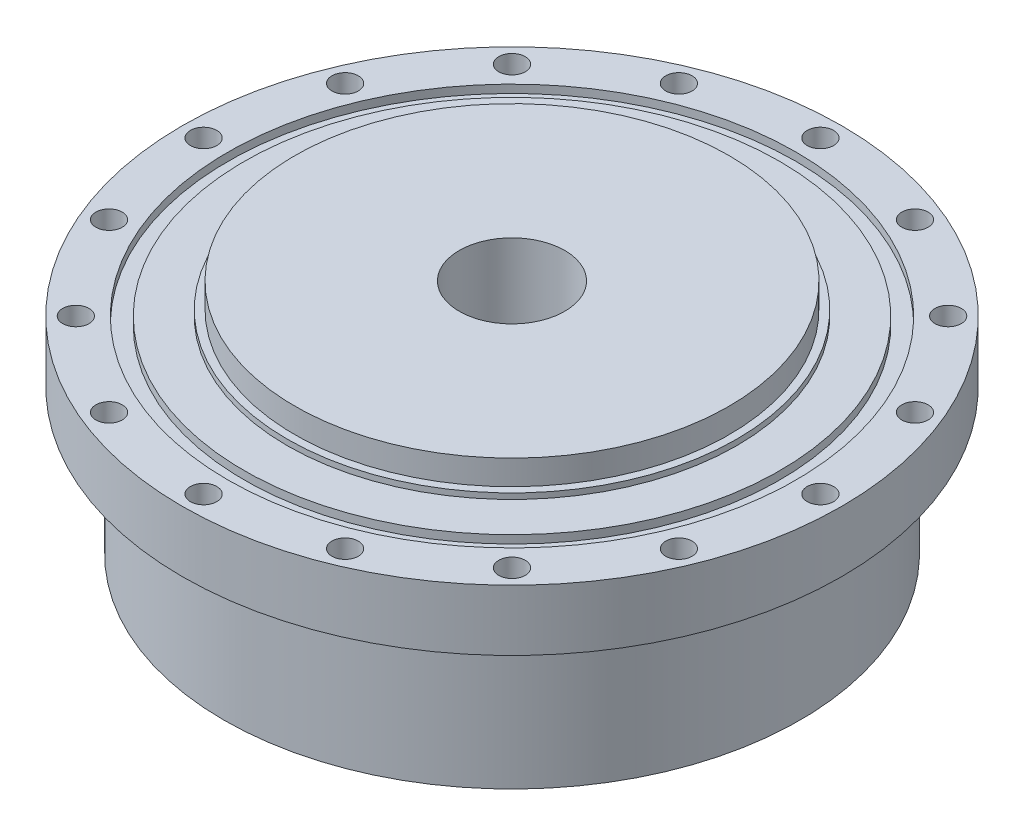
SolidWorks part; units mm, degrees
ref_plane "Front Plane" through (0, 0, 0) normal (0, 0, 1) x (1, 0, 0)
ref_plane "Top Plane" through (0, 0, 0) normal (0, 1, 0) x (1, 0, 0)
ref_plane "Right Plane" through (0, 0, 0) normal (1, 0, 0) x (0, 0, -1)
sketch "Sketch1" plane through (0, 0, 0) normal (0, 0, 1) x (1, 0, 0)
  line L0 (0, 0) -> (0, 283.109) construction
  line L1 (0, 0) -> (-122.5, 0)
  line L2 (-122.5, 0) -> (-122.5, 8.5)
  line L3 (-122.5, 8.5) -> (-142, 8.5)
  line L4 (-142, 8.5) -> (-142, 80)
  line L5 (-142, 80) -> (-162.5, 80)
  line L6 (-162.5, 80) -> (-162.5, 110)
  line L7 (-162.5, 110) -> (-140, 110)
  line L8 (-140, 110) -> (-140, 106)
  line L9 (-140, 106) -> (-132, 106)
  line L10 (-132, 106) -> (-132, 110)
  line L11 (-132, 110) -> (-110.75, 110)
  line L12 (-107, 112.8) -> (-107, 125)
  line L13 (-107, 125) -> (-26, 125)
  line L18 (0, 65) -> (0, 0)
  line L19 (-107, 112.8) -> (-110.75, 112.8)
  line L20 (-110.75, 112.8) -> (-110.75, 110)
  line L21 (-26, 125) -> (-26, 65)
  line L22 (-26, 65) -> (0, 65)
  dimension "D1" = 245
  dimension "D2" = 284
  dimension "D3" = 325
  dimension "D4" = 280
  dimension "D5" = 214
  dimension "D6" = 30
  dimension "D7" = 80
  dimension "D8" = 125
  dimension "D9" = 8.5
  dimension "D10" = 264
  dimension "D11" = 52
  dimension "D12" = 60
  dimension "D13" = 221.5
  dimension "D14" = 2.8
  dimension "D15" = 4
  dimension "D16" = 12.2
revolve "Revolve1" add sketch "Sketch1" angle 360 about L0
sketch "Sketch2" plane through (0, 0, 0) normal (0, -1, 0) x (1, 0, 0)
  line L0 (0, 0) -> (-111.28, -12.6788) construction
  line L1 (0, 0) -> (-111.28, 12.6788) construction
  line L2 (0, 0) -> (-111.28, -12.6788) construction
  line L3 (0, 0) -> (-105.5758, -37.3864) construction
  line L4 (0, 0) -> (-122.5, 0) construction
  line L5 (-84.6935, -14.9337) -> (0, 0) construction
  line L6 (0, 0) -> (-84.6935, 14.9337) construction
  circle A0 centre (0, 0) radius 112 construction
  circle A1 centre (-111.28, -12.6788) radius 5
  circle A2 centre (-111.28, 12.6788) radius 5
  circle A3 centre (-105.5758, 37.3864) radius 5
  circle A4 centre (-94.4598, 60.1776) radius 5
  circle A5 centre (-105.5758, -37.3864) radius 5
  circle A6 centre (-94.4598, -60.1776) radius 5
  circle A22 centre (0, 0) radius 122.5 construction
  circle A23 centre (99.3452, 51.7158) radius 5 [skipped]
  circle A24 centre (85.1655, 72.7382) radius 5 [skipped]
  circle A25 centre (66.6202, 90.032) radius 5 [skipped]
  circle A26 centre (44.6599, 102.7107) radius 5 [skipped]
  circle A27 centre (20.4104, 110.1245) radius 5 [skipped]
  circle A28 centre (-4.8854, 111.8934) radius 5 [skipped]
  circle A29 centre (-4.8854, -111.8934) radius 5 [skipped]
  circle A30 centre (20.4104, -110.1245) radius 5 [skipped]
  circle A31 centre (44.6599, -102.7107) radius 5 [skipped]
  circle A32 centre (66.6202, -90.032) radius 5 [skipped]
  circle A33 centre (85.1655, -72.7382) radius 5 [skipped]
  circle A34 centre (99.3452, -51.7158) radius 5 [skipped]
  circle A35 centre (99.3452, 51.7158) radius 5
  circle A36 centre (85.1655, 72.7382) radius 5
  circle A37 centre (66.6202, 90.032) radius 5
  circle A38 centre (44.6599, 102.7107) radius 5
  circle A39 centre (20.4104, 110.1245) radius 5
  circle A40 centre (-4.8854, 111.8934) radius 5
  circle A41 centre (-4.8854, -111.8934) radius 5
  circle A42 centre (20.4104, -110.1245) radius 5
  circle A43 centre (44.6599, -102.7107) radius 5
  circle A44 centre (66.6202, -90.032) radius 5
  circle A45 centre (85.1655, -72.7382) radius 5
  circle A46 centre (99.3452, -51.7158) radius 5
  circle A47 centre (0, 0) radius 86 construction
  circle A48 centre (-84.6935, 14.9337) radius 8
  circle A49 centre (-84.6935, -14.9337) radius 8
  circle A50 centre (55.2797, 65.8798) radius 8
  circle A51 centre (29.4137, 80.8136) radius 8
  circle A52 centre (29.4137, -80.8136) radius 8
  circle A53 centre (55.2797, -65.8798) radius 8
  point P46 (0, 0)
  point P52 (0, 0)
  point P86 (0, 0)
  dimension "D1" = 224
  dimension "D2" = 10
  dimension "D8" = 6.5
  dimension "D9" = 172
  dimension "D10" = 16
  dimension "D4" = 13
  dimension "D6" = 13
  dimension "D11" = 20
  dimension "D3" = 4
  dimension "D5" = 3
  dimension "D7" = 3
extrude "Cut-Extrude1" cut sketch "Sketch2" against normal blind 20
sketch "Sketch3" plane through (0, 80, 0) normal (0, -1, 0) x (1, 0, 0)
  circle A0 centre (0, 0) radius 152 construction
  circle A1 centre (0, 152) radius 6.5
  circle A2 centre (58.1679, 140.4297) radius 6.5
  circle A3 centre (107.4802, 107.4802) radius 6.5
  circle A4 centre (140.4297, 58.1679) radius 6.5
  circle A5 centre (152, 0) radius 6.5
  circle A6 centre (140.4297, -58.1679) radius 6.5
  circle A7 centre (107.4802, -107.4802) radius 6.5
  circle A8 centre (58.1679, -140.4297) radius 6.5
  circle A9 centre (0, -152) radius 6.5
  circle A10 centre (-58.1679, -140.4297) radius 6.5
  circle A11 centre (-107.4802, -107.4802) radius 6.5
  circle A12 centre (-140.4297, -58.1679) radius 6.5
  circle A13 centre (-152, 0) radius 6.5
  circle A14 centre (-140.4297, 58.1679) radius 6.5
  circle A15 centre (-107.4802, 107.4802) radius 6.5
  circle A16 centre (-58.1679, 140.4297) radius 6.5
  point P54 (0, 0)
  dimension "D1" = 304
  dimension "D2" = 13
  dimension "D3" = 16
extrude "Cut-Extrude2" cut sketch "Sketch3" against normal blind 40
sketch "Sketch4" plane through (0, 0, 0) normal (0, -1, 0) x (1, 0, 0)
  line L0 (193.3617, 664.9601) -> (1372.0283, 664.9601) construction
  line L1 (0, 0) -> (64, 0) construction
  line L2 (-32, 55.4256) -> (0, 0) construction
  line L3 (0, 0) -> (-32, -55.4256) construction
  arc A0 (20.2326, 60.7177) -> (-62.6994, 12.8369) centre (-32, 55.4256) ccw
  arc A1 (42.4668, -47.8808) -> (42.4668, 47.8808) centre (64, 0) ccw
  arc A2 (-62.6994, -12.8369) -> (20.2326, -60.7177) centre (-32, -55.4256) ccw
  arc A3 (-62.6994, 12.8369) -> (-62.6994, -12.8369) centre (0, 0) ccw
  circle A4 centre (0, 0) radius 122.5
  arc A6 (20.2326, -60.7177) -> (42.4668, -47.8808) centre (0, 0) ccw
  arc A7 (42.4668, 47.8808) -> (20.2326, 60.7177) centre (0, 0) ccw
  dimension "D1" = 105
  dimension "D2" = 245
  dimension "D3" = 128
  dimension "D4" = 120
  dimension "D5" = 120
extrude "Cut-Extrude3" cut sketch "Sketch4" against normal blind 3
sketch "Sketch7" plane through (0, 3, 0) normal (0, -1, 0) x (1, 0, 0)
  circle B0 centre (-105.5758, 37.3864) radius 5
  circle B1 centre (-111.28, 12.6788) radius 5
  circle B2 centre (-84.6935, 14.9337) radius 8
  circle B3 centre (0, 0) radius 122.5
  circle B4 centre (-84.6935, -14.9337) radius 8
  circle B5 centre (-105.5758, -37.3864) radius 5
  circle B6 centre (-111.28, -12.6788) radius 5
  arc B7 (20.2326, 60.7177) -> (-62.6994, 12.8369) centre (-32, 55.4256) ccw
  circle B8 centre (-94.4598, 60.1776) radius 5
  circle B9 centre (-4.8854, 111.8934) radius 5
  circle B10 centre (20.4104, 110.1245) radius 5
  circle B11 centre (-4.8854, -111.8934) radius 5
  circle B12 centre (20.4104, -110.1245) radius 5
  circle B13 centre (44.6599, -102.7107) radius 5
  circle B14 centre (66.6202, -90.032) radius 5
  circle B15 centre (85.1655, -72.7382) radius 5
  circle B16 centre (99.3452, -51.7158) radius 5
  circle B17 centre (55.2797, -65.8798) radius 8
  circle B18 centre (29.4137, -80.8136) radius 8
  circle B19 centre (-94.4598, -60.1776) radius 5
  arc B20 (-62.6994, 12.8369) -> (-62.6994, -12.8369) centre (0, 0) ccw
  arc B21 (-62.6994, -12.8369) -> (20.2326, -60.7177) centre (-32, -55.4256) ccw
  arc B22 (20.2326, -60.7177) -> (42.4668, -47.8808) centre (0, 0) ccw
  arc B23 (42.4668, -47.8808) -> (42.4668, 47.8808) centre (64, 0) ccw
  arc B24 (42.4668, 47.8808) -> (20.2326, 60.7177) centre (0, 0) ccw
  circle B25 centre (29.4137, 80.8136) radius 8
  circle B26 centre (55.2797, 65.8798) radius 8
  circle B27 centre (99.3452, 51.7158) radius 5
  circle B28 centre (85.1655, 72.7382) radius 5
  circle B29 centre (66.6202, 90.032) radius 5
  circle B30 centre (44.6599, 102.7107) radius 5
sketch_block_instance "Block1-1"
sketch_block "Block1"
